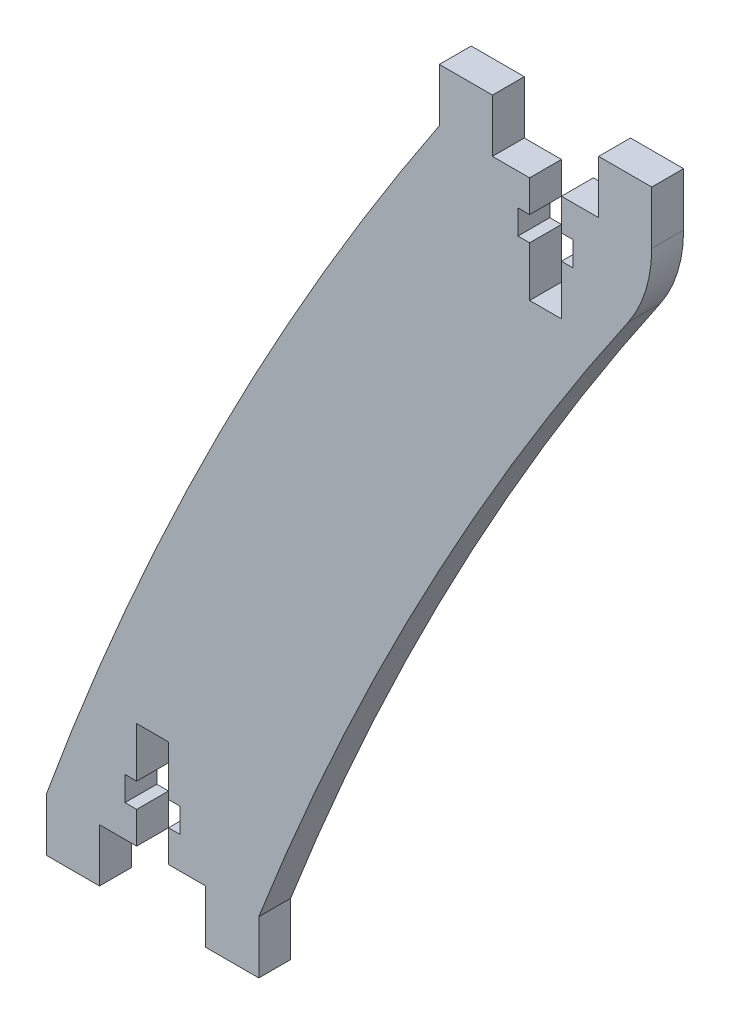
SolidWorks part; units mm, degrees
ref_plane "Front Plane" through (0, 0, 0) normal (0, 0, 1) x (1, 0, 0)
ref_plane "Top Plane" through (0, 0, 0) normal (0, 1, 0) x (1, 0, 0)
ref_plane "Right Plane" through (0, 0, 0) normal (1, 0, 0) x (0, 0, -1)
sketch "Sketch1" plane through (0, 0, 0) normal (0, 0, 1) x (1, 0, 0)
  line L0 (13, 0) -> (13, 73) construction
  line L1 (23, 0) -> (23, 65.2704) construction
  line L2 (13, 73) -> (70, 73) construction
  line L3 (13, 0) -> (21.9506, 24.5916) construction
  line L4 (0, 0) -> (61.5031, 0) construction
  line L5 (70, 73) -> (70, 49.2739) construction
  line L6 (60, 73) -> (60, 55.7792) construction
  line L7 (61.5, 73) -> (65, 73)
  line L8 (65, 78) -> (70, 78)
  line L9 (70, 78) -> (70, 73)
  line L10 (65, 78) -> (65, 73)
  line L11 (58.5, 73) -> (55, 73)
  line L12 (55, 73) -> (55, 78)
  line L13 (55, 78) -> (50, 78)
  line L14 (50, 78) -> (50, 73)
  line L15 (61.5, 73) -> (58.5, 73) construction
  line L16 (58.5, 73) -> (58.5, 70)
  line L17 (58.5, 67.7) -> (57.4, 67.7)
  line L18 (62.6, 70) -> (62.6, 67.7)
  line L19 (57.4, 70) -> (58.5, 70)
  line L20 (58.5, 67.7) -> (58.5, 63)
  line L21 (58.5, 63) -> (61.5, 63)
  line L22 (61.5, 63) -> (61.5, 67.7)
  line L23 (61.5, 70) -> (62.6, 70)
  line L24 (57.4, 67.7) -> (57.4, 70)
  line L25 (62.6, 67.7) -> (61.5, 67.7)
  line L26 (61.5, 70) -> (61.5, 73)
  line L27 (60, 63) -> (60, 73) construction
  line L28 (23, 0) -> (23, 11.2208) construction
  line L29 (21.5, 0) -> (18, 0)
  line L30 (18, -5) -> (13, -5)
  line L31 (13, -5) -> (13, 0)
  line L32 (18, -5) -> (18, 0)
  line L33 (24.5, 0) -> (28, 0)
  line L34 (28, 0) -> (28, -5)
  line L35 (28, -5) -> (33, -5)
  line L36 (33, -5) -> (33, 0)
  line L37 (21.5, 0) -> (24.5, 0) construction
  line L38 (24.5, 0) -> (24.5, 3)
  line L39 (24.5, 5.3) -> (25.6, 5.3)
  line L40 (20.4, 3) -> (20.4, 5.3)
  line L41 (25.6, 3) -> (24.5, 3)
  line L42 (24.5, 5.3) -> (24.5, 10)
  line L43 (24.5, 10) -> (21.5, 10)
  line L44 (21.5, 10) -> (21.5, 5.3)
  line L45 (21.5, 3) -> (20.4, 3)
  line L46 (25.6, 5.3) -> (25.6, 3)
  line L47 (20.4, 5.3) -> (21.5, 5.3)
  line L48 (21.5, 3) -> (21.5, 0)
  line L49 (23, 10) -> (23, 0) construction
  arc A0 (13, 0) -> (50, 73) centre (334.0877, -116.8664) cw
  arc A1 (70, 73) -> (67.7946, 65.889) centre (57.4332, 73) cw
  arc A2 (67.7946, 65.889) -> (33, 0) centre (334.0877, -116.8664) ccw
  dimension "D1" = 73
  dimension "D2" = 23
  dimension "D3" = 5.2
  dimension "D4" = 20
  dimension "D5" = 10
  dimension "D6" = 5
  dimension "D7" = 5
  dimension "D8" = 3
  dimension "D9" = 2.3
  dimension "D10" = 3
  dimension "D11" = 10
  dimension "D12" = 10
  dimension "D13" = 5
  dimension "D14" = 5
  dimension "D15" = 5.2
  dimension "D16" = 3
  dimension "D17" = 2.3
  dimension "D18" = 3
  dimension "D19" = 10
  dimension "D20" = 60
extrude "Boss-Extrude1" add sketch "Sketch1" along normal blind 3
